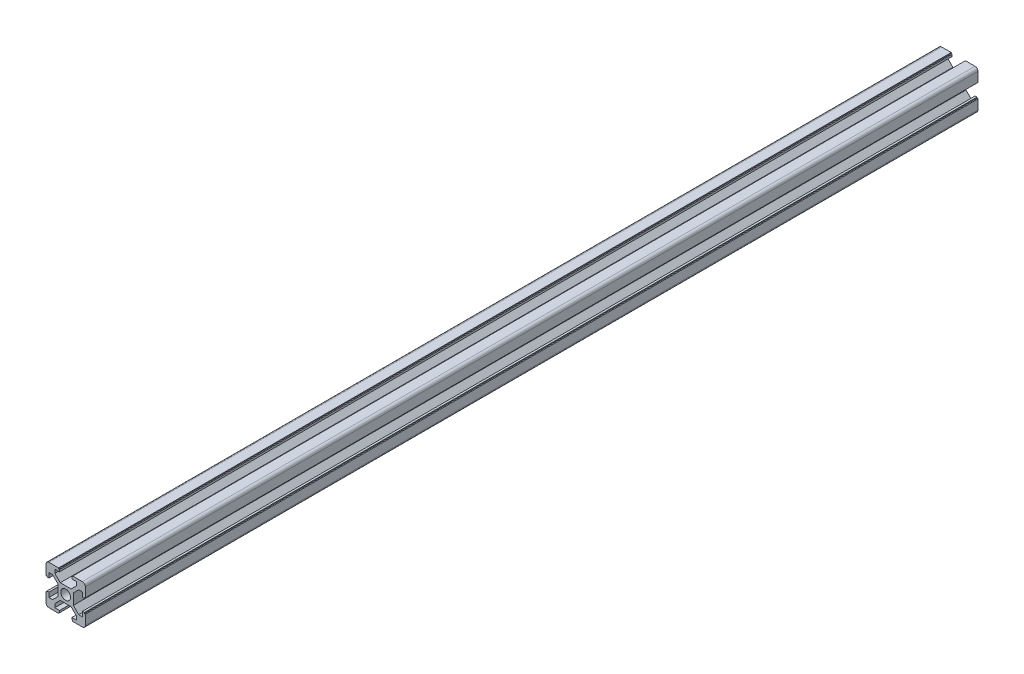
SolidWorks part; units mm, degrees
ref_plane "Plane1" through (0, 0, 0) normal (0, 0, 1) x (1, 0, 0)
ref_plane "Plane2" through (0, 0, 0) normal (0, 1, 0) x (1, 0, 0)
ref_plane "Plane3" through (0, 0, 0) normal (1, 0, 0) x (0, 0, -1)
sketch "Sketch1" plane through (0, 0, 0) normal (0, 0, 1) x (1, 0, 0)
  line L0 (-3.6, 10) -> (-3.6, 9.5)
  line L1 (-3.6, 9.5) -> (-3.1, 9.5)
  line L2 (-3.1, 9.5) -> (-3.1, 8.5)
  line L3 (-3.1, 8.5) -> (-5.5, 8.5)
  line L4 (-8.5, -10) -> (-3.6, -10)
  line L5 (-10, -8.5) -> (-10, -3.6)
  line L6 (8.5, 10) -> (3.6, 10)
  line L7 (10, 8.5) -> (10, 3.6)
  line L8 (0, 14.8756) -> (0, 0) construction
  line L9 (0, 0) -> (14.1675, 0) construction
  line L10 (-5.5, 8.5) -> (-5.5, 6.65)
  line L11 (-5.5, 6.65) -> (-2.75, 3.9)
  line L12 (-2.75, 3.9) -> (2.75, 3.9)
  line L13 (5.5, 6.65) -> (2.75, 3.9)
  line L14 (5.5, 8.5) -> (5.5, 6.65)
  line L15 (3.1, 8.5) -> (5.5, 8.5)
  line L16 (3.1, 9.5) -> (3.1, 8.5)
  line L17 (3.6, 9.5) -> (3.1, 9.5)
  line L18 (3.6, 10) -> (3.6, 9.5)
  line L19 (-3.6, 10) -> (-8.5, 10)
  line L20 (10, 3.6) -> (9.5, 3.6)
  line L21 (9.5, 3.6) -> (9.5, 3.1)
  line L22 (9.5, 3.1) -> (8.5, 3.1)
  line L23 (8.5, 3.1) -> (8.5, 5.5)
  line L24 (8.5, 5.5) -> (6.65, 5.5)
  line L25 (6.65, 5.5) -> (3.9, 2.75)
  line L26 (3.9, 2.75) -> (3.9, -2.75)
  line L27 (6.65, -5.5) -> (3.9, -2.75)
  line L28 (8.5, -5.5) -> (6.65, -5.5)
  line L29 (8.5, -3.1) -> (8.5, -5.5)
  line L30 (9.5, -3.1) -> (8.5, -3.1)
  line L31 (9.5, -3.6) -> (9.5, -3.1)
  line L32 (10, -3.6) -> (9.5, -3.6)
  line L33 (3.6, -10) -> (3.6, -9.5)
  line L34 (3.6, -9.5) -> (3.1, -9.5)
  line L35 (3.1, -9.5) -> (3.1, -8.5)
  line L36 (3.1, -8.5) -> (5.5, -8.5)
  line L37 (5.5, -8.5) -> (5.5, -6.65)
  line L38 (5.5, -6.65) -> (2.75, -3.9)
  line L39 (2.75, -3.9) -> (-2.75, -3.9)
  line L40 (-5.5, -6.65) -> (-2.75, -3.9)
  line L41 (-5.5, -8.5) -> (-5.5, -6.65)
  line L42 (-3.1, -8.5) -> (-5.5, -8.5)
  line L43 (-3.1, -9.5) -> (-3.1, -8.5)
  line L44 (-3.6, -9.5) -> (-3.1, -9.5)
  line L45 (-3.6, -10) -> (-3.6, -9.5)
  line L46 (-10, -3.6) -> (-9.5, -3.6)
  line L47 (-9.5, -3.6) -> (-9.5, -3.1)
  line L48 (-9.5, -3.1) -> (-8.5, -3.1)
  line L49 (-8.5, -3.1) -> (-8.5, -5.5)
  line L50 (-8.5, -5.5) -> (-6.65, -5.5)
  line L51 (-6.65, -5.5) -> (-3.9, -2.75)
  line L52 (-3.9, -2.75) -> (-3.9, 2.75)
  line L53 (-6.65, 5.5) -> (-3.9, 2.75)
  line L54 (-8.5, 5.5) -> (-6.65, 5.5)
  line L55 (-8.5, 3.1) -> (-8.5, 5.5)
  line L56 (-9.5, 3.1) -> (-8.5, 3.1)
  line L57 (-9.5, 3.6) -> (-9.5, 3.1)
  line L58 (-10, 3.6) -> (-9.5, 3.6)
  line L59 (3.6, -10) -> (8.5, -10)
  line L60 (-10, 3.6) -> (-10, 8.5)
  line L61 (10, -3.6) -> (10, -8.5)
  circle A0 centre (0, 0) radius 2.5
  arc A1 (-10, 8.5) -> (-8.5, 10) centre (-8.5, 8.5) cw
  arc A2 (10, 8.5) -> (8.5, 10) centre (8.5, 8.5) ccw
  arc A3 (-8.5, -10) -> (-10, -8.5) centre (-8.5, -8.5) cw
  arc A4 (8.5, -10) -> (10, -8.5) centre (8.5, -8.5) ccw
  point P0 (-10, 0)
  point P1 (10, 0)
  point P2 (0, 10)
  point P3 (0, -10)
  point P4 (0, 0)
  point P5 (-10, -10)
  point P6 (10, -10)
  point P7 (10, 10)
  point P8 (-10, 10)
  point P36 (-10, 10)
  point P39 (10, 10)
extrude "凸台-拉伸1" add sketch "Sketch1" along normal blind 454
